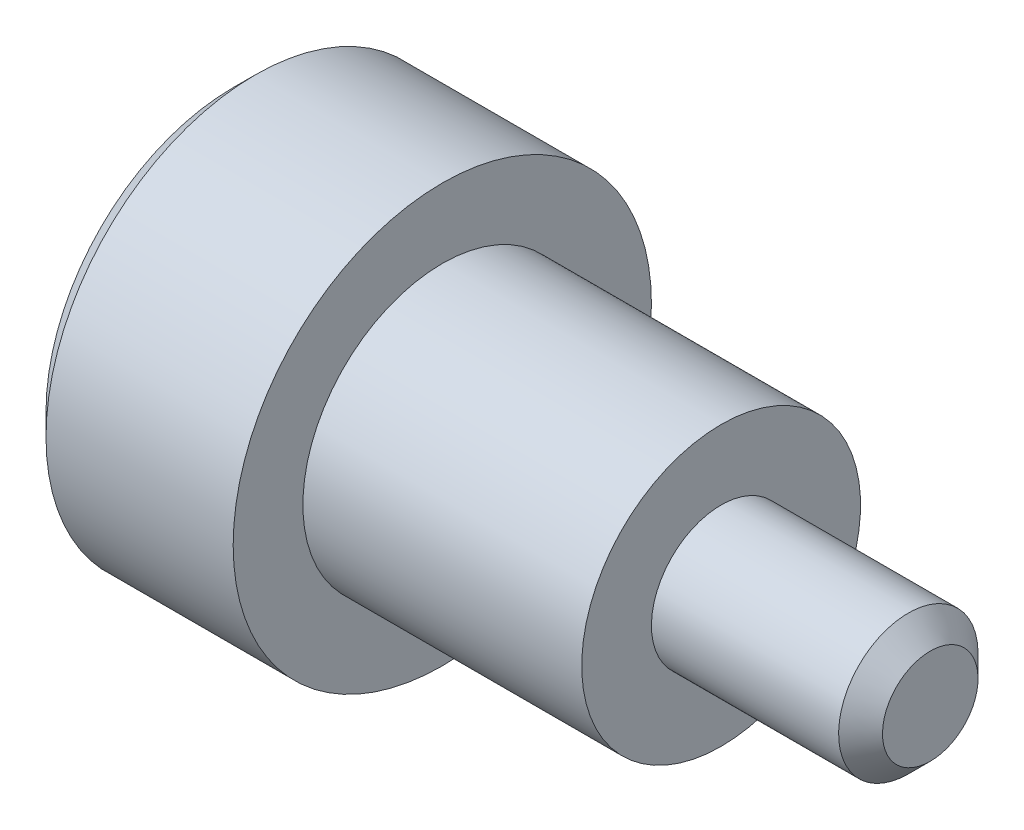
SolidWorks part; units mm, degrees
material "PBT General Purpose"
ref_plane "Front Plane" through (0, 0, 0) normal (0, 0, 1) x (1, 0, 0)
ref_plane "Top Plane" through (0, 0, 0) normal (0, 1, 0) x (1, 0, 0)
ref_plane "Right Plane" through (0, 0, 0) normal (1, 0, 0) x (0, 0, -1)
ref_plane "Plane1" through (0, 0, 0) normal (0, 0, 1) x (1, 0, 0)
sketch "Sketch1" plane through (0, 0, 0) normal (0, 0, 1) x (1, 0, 0)
  line L0 (0, 0) -> (0, 4.2625)
  line L1 (0, 4.2625) -> (0.5, 4.7625)
  line L2 (0.5, 4.7625) -> (4.7625, 4.7625)
  line L3 (4.7625, 4.7625) -> (4.7625, 3.175)
  line L4 (4.7625, 3.175) -> (11.1125, 3.175)
  line L5 (11.1125, 3.175) -> (11.1125, 1.5875)
  line L6 (11.1125, 1.5875) -> (15.375, 1.5875)
  line L7 (15.375, 1.5875) -> (15.875, 1.0875)
  line L8 (15.875, 1.0875) -> (15.875, 0)
  line L9 (15.875, 0) -> (0, 0)
  line L10 (15.875, 0) -> (0, 0) construction
  dimension "D1" = 4.7625
  dimension "D2" = 4.7625
  dimension "D3" = 6.35
  dimension "D4" = 3.175
  dimension "D5" = 4.7625
  dimension "D6" = 225
  dimension "D7" = 0.5
  dimension "D8" = 1.5875
  dimension "D9" = 225
revolve "Revolve1" add sketch "Sketch1" angle 360 about L10
ref_plane "Plane2" through (0, 0, 0) normal (0, 0, 1) x (1, 0, 0)
sketch "Sketch2" plane through (0, 0, 0) normal (0, 0, 1) x (1, 0, 0)
  line L0 (0, 0) -> (0, 1)
  line L1 (0, 1) -> (2, 1)
  line L2 (2, 1) -> (2.5774, 0)
  line L3 (2.5774, 0) -> (0, 0)
  line L4 (2.5774, 0) -> (0, 0) construction
  dimension "D1" = 1
  dimension "D2" = 2.5774
  dimension "D3" = 2
revolve "Cut-Revolve1" cut sketch "Sketch2" angle 360 about L4
sketch "Sketch3" plane through (0, 0, 0) normal (1, 0, 0) x (0, 0, -1)
  line L0 (-1, 0.5774) -> (-1, -0.5774)
  line L1 (-1, -0.5774) -> (0, -1.1547)
  line L2 (0, -1.1547) -> (1, -0.5774)
  line L3 (1, -0.5774) -> (1, 0.5774)
  line L4 (1, 0.5774) -> (0, 1.1547)
  line L5 (0, 1.1547) -> (-1, 0.5774)
extrude "Cut-Extrude1" cut sketch "Sketch3" along normal blind 2
